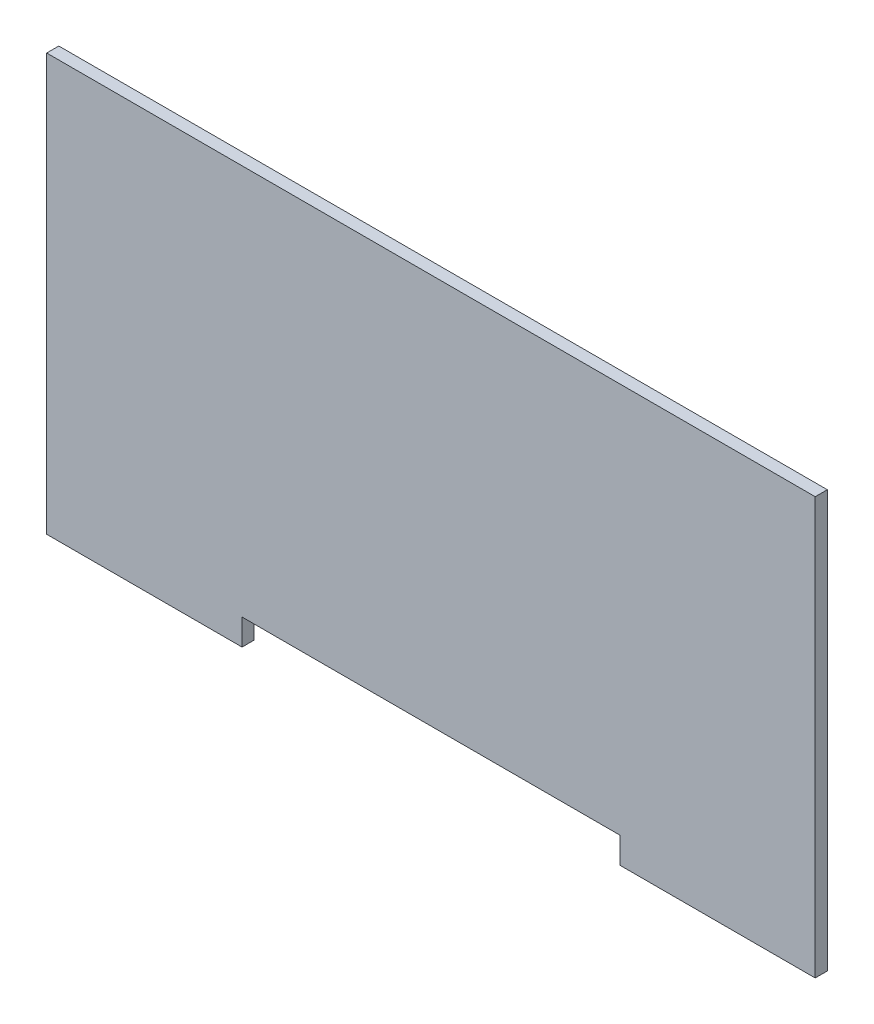
SolidWorks part; units mm, degrees
material "Pine"
ref_plane "Front Plane" through (0, 0, 0) normal (0, 0, 1) x (1, 0, 0)
ref_plane "Top Plane" through (0, 0, 0) normal (0, 1, 0) x (1, 0, 0)
ref_plane "Right Plane" through (0, 0, 0) normal (1, 0, 0) x (0, 0, -1)
sketch "Sketch1" plane through (0, 0, 0) normal (0, 0, 1) x (1, 0, 0)
  line L1 (-147.5, 75) -> (147.5, 75)
  line L2 (-147.5, 75) -> (-147.5, -75)
  line L3 (-147.5, -75) -> (147.5, -75)
  line L4 (147.5, 75) -> (147.5, -75)
  line L5 (-147.5, 75) -> (147.5, -75) construction
  line L6 (-147.5, -75) -> (147.5, 75) construction
  line L7 (-147.5, -75) -> (-72.5, -75)
  line L8 (-147.5, -75) -> (-147.5, -85)
  line L9 (-147.5, -85) -> (-72.5, -85)
  line L10 (-72.5, -75) -> (-72.5, -85)
  line L11 (147.5, -75) -> (72.5, -75)
  line L12 (147.5, -75) -> (147.5, -85)
  line L13 (147.5, -85) -> (72.5, -85)
  line L14 (72.5, -75) -> (72.5, -85)
  point P0 (0, 0)
  dimension "D1" = 295
  dimension "D2" = 150
  dimension "8" = 10
  dimension "D4" = 75
  dimension "D5" = 10
  dimension "D6" = 75
extrude "Boss-Extrude1" add sketch "Sketch1" along normal blind 4.65 contours L4 L1 L2 L3 | L3 L14 L13 L12 | L8 L9 L10 L7
